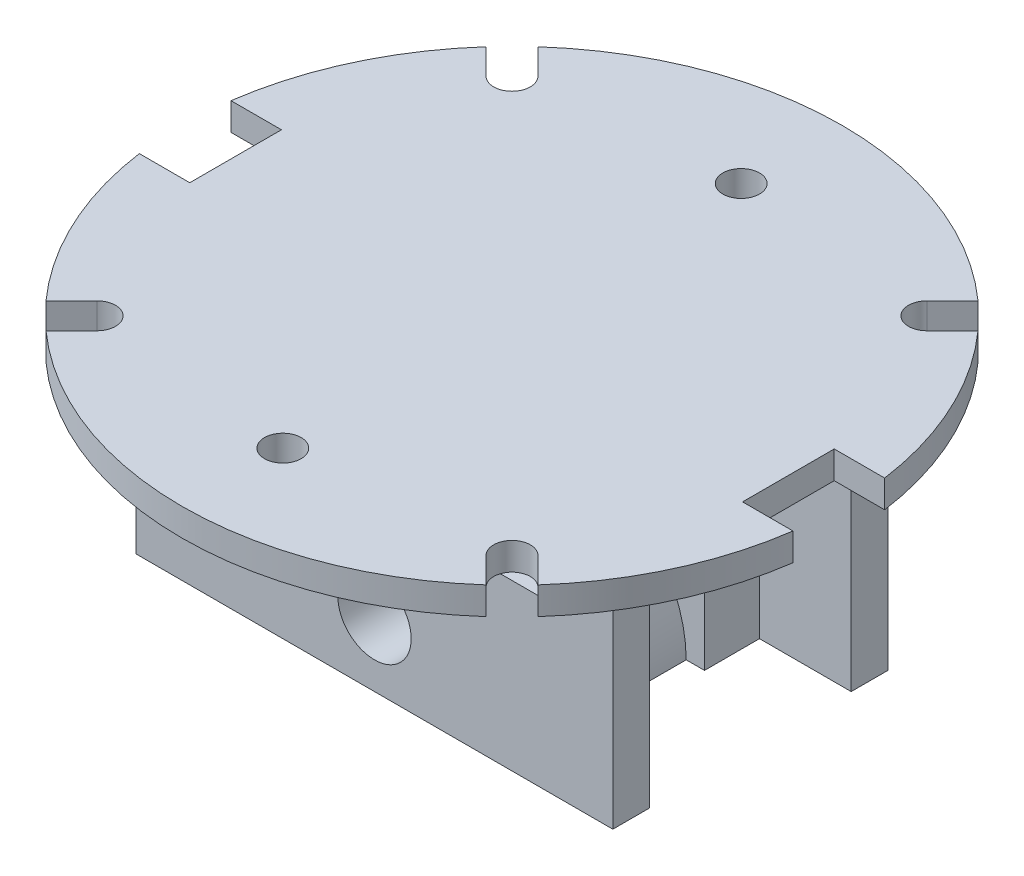
SolidWorks part; units mm, degrees
ref_plane "前视基准面" through (0, 0, 0) normal (0, 0, 1) x (1, 0, 0)
ref_plane "上视基准面" through (0, 0, 0) normal (0, 1, 0) x (1, 0, 0)
ref_plane "右视基准面" through (0, 0, 0) normal (1, 0, 0) x (0, 0, -1)
other "Configuration Table"
sketch "草图1" plane through (0, 0, 0) normal (0, 1, 0) x (1, 0, 0)
  line L0 (13, 5.5) -> (8, 5.5)
  line L1 (-13, 7.5) -> (13, 7.5)
  line L2 (-13, 7.5) -> (-13, 5.5)
  line L3 (-13, -7.5) -> (13, -7.5)
  line L4 (13, 7.5) -> (13, 5.5)
  line L5 (-13, 7.5) -> (13, -7.5) construction
  line L6 (-13, -7.5) -> (13, 7.5) construction
  line L7 (8, 5.5) -> (8, -5.5)
  line L8 (8, -5.5) -> (13, -5.5)
  line L9 (-13, 5.5) -> (-8, 5.5)
  line L10 (-8, 5.5) -> (-8, -5.5)
  line L11 (-8, -5.5) -> (-13, -5.5)
  line L12 (13, -5.5) -> (13, -7.5)
  line L13 (-13, -5.5) -> (-13, -7.5)
  point P0 (0, 0)
  dimension "D1" = 26
  dimension "D2" = 15
  dimension "D3" = 5
  dimension "D4" = 5
  dimension "D5" = 11
  dimension "D6" = 11
  dimension "D7" = 2
extrude "凸台-拉伸1" add sketch "草图1" along normal blind 12.5
sketch "草图2" plane through (0, 0, 0) normal (0, 0, 1) x (1, 0, 0)
  line L0 (0, 0) -> (0, 3.5) construction
  circle A0 centre (0, 3.5) radius 2
  dimension "D2" = 4
  dimension "D1" = 3.5
extrude "切除-拉伸1" cut sketch "草图2" against normal through all and the other way through all
sketch "草图3" plane through (0, 0, 0) normal (0, 0, 1) x (1, 0, 0)
  line L0 (0, 12.5) -> (0, 10) construction
  line L1 (-13, 12.5) -> (13, 12.5) construction
  line L2 (-10.5, 10) -> (-13, 10) construction
  line L3 (-13, 12.5) -> (-13, 0) construction
  line L4 (-10.5, 10) -> (-2, 10) construction
  line L5 (-10.5, 11) -> (-2, 11)
  line L6 (-2, 9) -> (-10.5, 9)
  line L7 (10.5, 10) -> (2, 10) construction
  line L8 (10.5, 10) -> (13, 10) construction
  line L9 (2, 9) -> (10.5, 9)
  line L10 (10.5, 11) -> (2, 11)
  arc A0 (-10.5, 11) -> (-10.5, 9) centre (-10.5, 10) ccw
  arc A1 (-2, 9) -> (-2, 11) centre (-2, 10) ccw
  arc A2 (2, 9) -> (2, 11) centre (2, 10) cw
  arc A3 (10.5, 11) -> (10.5, 9) centre (10.5, 10) cw
  dimension "D2" = 2
  dimension "D6" = 2
  dimension "D1" = 2.5
  dimension "D3" = 2.5
  dimension "D4" = 2.5
  dimension "D5" = 8.5
extrude "切除-拉伸2" cut sketch "草图3" against normal through all and the other way through all
sketch "草图5" plane through (0, 0, 0) normal (0, 1, 0) x (1, 0, 0)
  line L0 (8, -5.5) -> (8, 5.5) construction
  line L1 (-8, 2.5) -> (8, 2.5)
  line L2 (-8, 2.5) -> (-8, -2.5)
  line L3 (-8, -2.5) -> (8, -2.5)
  line L4 (8, 2.5) -> (8, -2.5)
  line L5 (-8, 2.5) -> (8, -2.5) construction
  line L6 (-8, -2.5) -> (8, 2.5) construction
  point P0 (0, 0)
  dimension "D1" = 5
extrude "切除-拉伸4" cut sketch "草图5" against normal blind 5.5 from surface at 12.5 starting at face at (0, 12.5, 0)
sketch "草图6" plane through (0, 0, 0) normal (0, 0, 1) x (1, 0, 0)
  line L0 (-8, 0) -> (-8, 7)
  line L1 (-8, 9) -> (-8, 0) construction
  line L2 (-8, 7) -> (8, 7)
  line L3 (8, 7) -> (8, 0)
  line L4 (8, 0) -> (13, 0) construction
  line L5 (8, 9) -> (8, 0) construction
  line L6 (8, 0) -> (7, 0)
  line L7 (-8, 0) -> (-7, 0)
  arc A0 (7, 0) -> (-7, 0) centre (0, 0) ccw
  dimension "D1" = 14
  dimension "D2" = 7
extrude "切除-拉伸5" cut sketch "草图6" against normal blind 2.5 and the other way blind 2.5 contours A0 L6 L3 L2 | A0 L2 L0 L7
sketch "草图7" plane through (0, 0, 0) normal (0, 1, 0) x (1, 0, 0)
  line L0 (-1000, 0) -> (49000, 0) construction
  line L2 (17.8255, 2.5) -> (15.0755, 2.5)
  line L3 (15.0755, -2.5) -> (17.8255, -2.5)
  line L4 (15.0755, 2.5) -> (15.0755, -2.5)
  line L5 (0, -1000) -> (0, 49000) construction
  line L6 (-15.0755, 2.5) -> (-15.0755, -2.5)
  line L7 (-15.0755, -2.5) -> (-17.8255, -2.5)
  line L8 (-17.8255, 2.5) -> (-15.0755, 2.5)
  arc A0 (17.8255, 2.5) -> (-17.8255, 2.5) centre (0, 0) ccw
  arc A1 (-17.8255, -2.5) -> (17.8255, -2.5) centre (0, 0) ccw
  point P8 (17.8255, 0)
  dimension "D1" = 36
  dimension "D2" = 5
  dimension "D3" = 2.75
  dimension "D4" = 2.75
extrude "凸台-拉伸5" add sketch "草图7" along normal blind 1.5 from surface at 12.5 starting at face at (0, 12.5, -5.25)
ref_plane "基准面1" through (0, 0, -2.5) normal (0, 0, 1) x (1, 0, 0)
ref_plane "基准面2" through (0, 0, 2.5) normal (0, 0, -1) x (-1, 0, 0)
sketch "草图8" plane through (0, 0, 0) normal (0, 1, 0) x (1, 0, 0)
  line L0 (0, 12.5) -> (0, -12.5) construction
  circle A0 centre (0, 12.5) radius 1
  circle A1 centre (0, -12.5) radius 1
  point P4 (0, 0)
  dimension "D2" = 2
  dimension "D3" = 2
  dimension "D1" = 25
extrude "切除-拉伸6" cut sketch "草图8" against normal up to next from surface
sketch "草图9" plane through (0, 0, 0) normal (0, 1, 0) x (1, 0, 0)
  line L0 (-707.1068, -707.1068) -> (34648.2323, 34648.2323) construction
  line L1 (707.1068, -707.1068) -> (-34648.2323, 34648.2323) construction
  line L2 (-11.3137, 11.3137) -> (-12.7279, 12.7279) construction
  line L3 (-12.0208, 10.6066) -> (-13.435, 12.0208)
  line L4 (-10.6066, 12.0208) -> (-12.0208, 13.435)
  line L5 (11.3137, -11.3137) -> (12.7279, -12.7279) construction
  line L6 (10.6066, -12.0208) -> (12.0208, -13.435)
  line L7 (12.0208, -10.6066) -> (13.435, -12.0208)
  line L8 (-1000, 0) -> (49000, 0) construction
  line L9 (-11.3137, -11.3137) -> (-12.7279, -12.7279) construction
  line L10 (-12.0208, -10.6066) -> (-13.435, -12.0208)
  line L11 (-10.6066, -12.0208) -> (-12.0208, -13.435)
  line L12 (11.3137, 11.3137) -> (12.7279, 12.7279) construction
  line L13 (10.6066, 12.0208) -> (12.0208, 13.435)
  line L14 (12.0208, 10.6066) -> (13.435, 12.0208)
  arc A0 (-12.0208, 10.6066) -> (-10.6066, 12.0208) centre (-11.3137, 11.3137) ccw
  arc A1 (-12.0208, 13.435) -> (-13.435, 12.0208) centre (-12.7279, 12.7279) ccw
  arc A2 (10.6066, -12.0208) -> (12.0208, -10.6066) centre (11.3137, -11.3137) cw
  arc A3 (13.435, -12.0208) -> (12.0208, -13.435) centre (12.7279, -12.7279) cw
  arc A4 (-12.0208, -10.6066) -> (-10.6066, -12.0208) centre (-11.3137, -11.3137) cw
  arc A5 (-12.0208, -13.435) -> (-13.435, -12.0208) centre (-12.7279, -12.7279) cw
  arc A6 (10.6066, 12.0208) -> (12.0208, 10.6066) centre (11.3137, 11.3137) ccw
  arc A7 (13.435, 12.0208) -> (12.0208, 13.435) centre (12.7279, 12.7279) ccw
  point P7 (-12.0208, 12.0208)
  point P12 (-12.7279, 11.3137)
  point P15 (12.0208, -12.0208)
  point P24 (-12.0208, -12.0208)
  point P31 (12.0208, 12.0208)
  dimension "D1" = 2
  dimension "D2" = 2
  dimension "D3" = 17
extrude "切除-拉伸7" cut sketch "草图9" against normal up to surface (1.5 mm away) from surface at 14 up to face at (0, 12.5, -11.5) starting at face at (0, 14, -11.5)
equation "\"2、\"=8"
